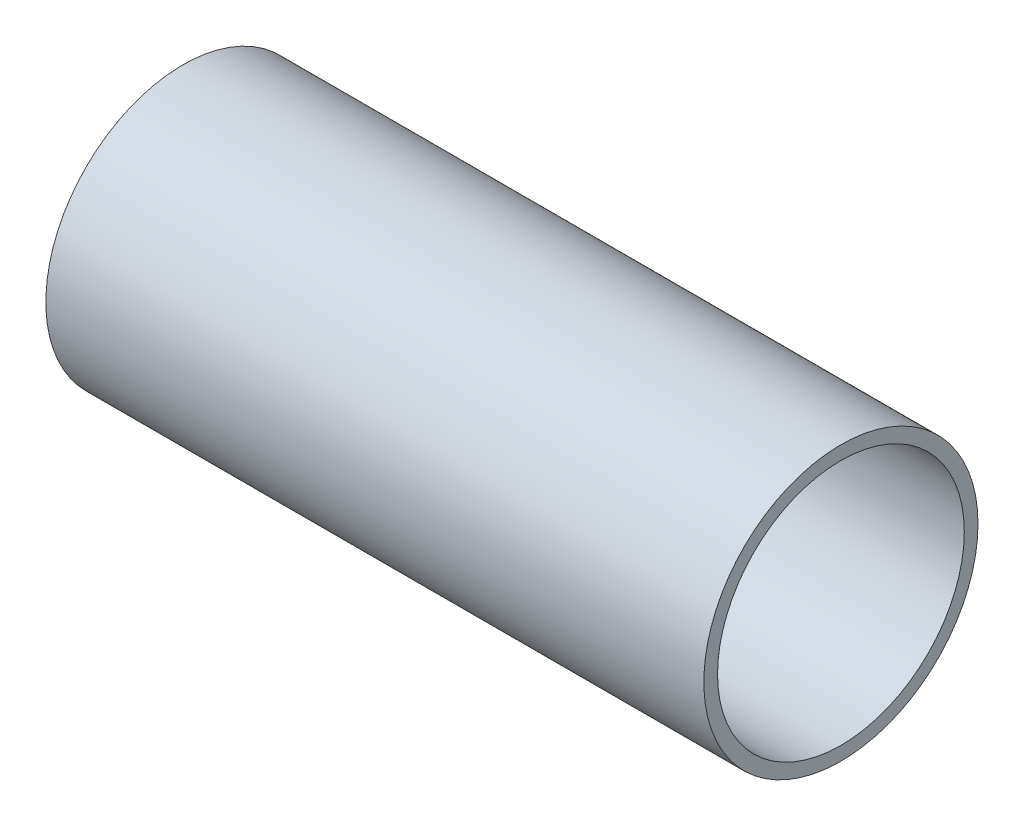
SolidWorks part; units mm, degrees
ref_plane "front" through (0, 0, 0) normal (0, 0, 1) x (1, 0, 0)
ref_plane "top" through (0, 0, 0) normal (0, 1, 0) x (1, 0, 0)
ref_plane "right" through (0, 0, 0) normal (1, 0, 0) x (0, 0, -1)
sketch "Sketch1" plane through (0, 0, 0) normal (1, 0, 0) x (0, 0, -1)
  circle A0 centre (0, 0) radius 31.75
  circle A1 centre (0, 0) radius 28.575
  dimension "D2" = 63.5
  dimension "D1" = 3.175
extrude "Extrude1" add sketch "Sketch1" against normal blind 152.4
